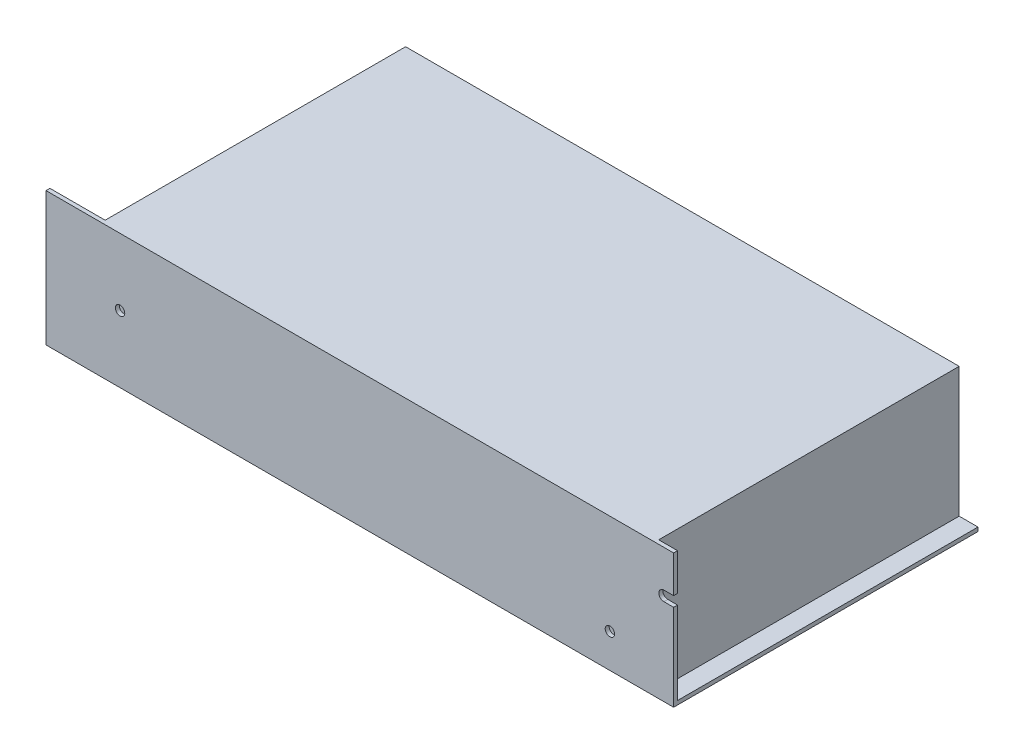
SolidWorks part; units mm, degrees
material "Stal węglowa"
ref_plane "Front" through (0, 0, 0) normal (0, 0, 1) x (1, 0, 0)
ref_plane "Top" through (0, 0, 0) normal (0, 1, 0) x (1, 0, 0)
ref_plane "Right" through (0, 0, 0) normal (1, 0, 0) x (0, 0, -1)
sketch "Szkic1" plane through (0, 0, 0) normal (0, 1, 0) x (1, 0, 0)
  line L1 (-60.5469, 54.8828) -> (139.4531, 54.8828)
  line L2 (-60.5469, 54.8828) -> (-60.5469, -42.1172)
  line L3 (-60.5469, -42.1172) -> (139.4531, -42.1172)
  line L4 (139.4531, 54.8828) -> (139.4531, -42.1172)
  dimension "D1" = 200
  dimension "D2" = 97
extrude "Dodanie-wyciągnięcie1" add sketch "Szkic1" along normal blind 1.25
sketch "Szkic2" plane through (0, 0, 0) normal (0, -1, 0) x (1, 0, 0)
  line L0 (-60.5469, 42.1172) -> (139.4531, 42.1172) construction
  line L1 (-60.5469, 42.1172) -> (139.4531, 42.1172)
  line L2 (-60.5469, 42.1172) -> (-60.5469, 40.8672)
  line L3 (-60.5469, 40.8672) -> (139.4531, 40.8672)
  line L4 (139.4531, 42.1172) -> (139.4531, 40.8672)
  line L5 (-60.5469, -54.8828) -> (-60.5469, 42.1172) construction
  line L6 (139.4531, 42.1172) -> (139.4531, -54.8828) construction
  dimension "D1" = 1.25
extrude "Dodanie-wyciągnięcie2" add sketch "Szkic2" against normal blind 42.6
sketch "Szkic3" plane through (0, 0, 42.1172) normal (0, 0, 1) x (1, 0, 0)
  line L0 (148.6314, 30.8) -> (134.7531, 30.8) construction
  line L1 (139.4531, 42.6) -> (-60.5469, 42.6) construction
  line L2 (151.1568, 27.6) -> (134.7531, 27.6) construction
  line L3 (134.7531, 30.8) -> (134.7531, 27.6) construction
  line L4 (139.4531, 42.6) -> (139.4531, 0) construction
  line L5 (134.7531, 29.2) -> (145.9475, 29.2) construction
  line L6 (136.3531, 26.4846) -> (136.3531, 33.5389) construction
  line L7 (136.3531, 30.8) -> (139.4531, 30.8)
  line L8 (139.4531, 30.8) -> (139.4531, 27.6)
  line L9 (139.4531, 27.6) -> (136.3531, 27.6)
  line L10 (120.6531, 73.2747) -> (120.6531, -18.7111) construction
  line L11 (63.995, 12.3) -> (238.0814, 12.3) construction
  line L12 (97.5718, 9.3) -> (153.7311, 9.3) construction
  line L13 (117.6531, 52.937) -> (117.6531, -10.3506) construction
  line L14 (120.6531, 9.3) -> (117.6531, 12.3) construction
  line L16 (-60.5469, 42.6) -> (-60.5469, 0) construction
  line L17 (-38.4469, 58.4899) -> (-38.4469, -5.7299) construction
  line L18 (-35.4469, 60.1177) -> (-35.4469, -5.7299) construction
  line L19 (-35.4469, 21.3) -> (-38.4469, 21.3) construction
  arc A2 (136.3531, 30.8) -> (136.3531, 27.6) centre (136.3531, 29.2) ccw
  circle A3 centre (119.1531, 10.8) radius 1.5
  circle A4 centre (-36.9469, 21.3) radius 1.5
  dimension "D1" = 11.8
  dimension "D2" = 3.2
  dimension "D3" = 4.7
  dimension "D4" = 1.6
  dimension "D5" = 18.8
  dimension "D6" = 30.3
  dimension "D7" = 3
  dimension "D8" = 3
  dimension "D9" = 22.1
  dimension "D10" = 3
sketch "Szkic4" plane through (0, 0, 0) normal (0, -1, 0) x (1, 0, 0)
  line L0 (123.1531, -54.8828) -> (123.1531, 47.2519) construction
  line L1 (139.4531, -54.8828) -> (-60.5469, -54.8828) construction
  line L2 (139.4531, 42.1172) -> (139.4531, -54.8828) construction
  line L3 (120.1531, 42.1172) -> (120.1531, -54.8828) construction
  line L4 (-60.5469, 42.1172) -> (139.4531, 42.1172) construction
  line L5 (139.4531, -6.3828) -> (-60.5469, -6.3828) construction
  line L6 (-60.5469, -54.8828) -> (-60.5469, 42.1172) construction
  line L7 (123.1531, -37.1328) -> (120.1531, -37.1328) construction
  line L8 (120.1531, -40.1328) -> (123.1531, -40.1328) construction
  line L9 (123.1531, 24.3672) -> (120.1531, 24.3672) construction
  line L10 (123.1531, -37.1328) -> (120.1531, -40.1328) construction
  line L11 (120.1531, 27.3672) -> (123.1531, 27.3672) construction
  line L12 (123.1531, 27.3672) -> (120.1531, 24.3672) construction
  line L13 (121.6531, -38.6328) -> (-104.4577, -38.6328) construction
  line L14 (121.6531, 25.8672) -> (-154.3123, 25.8672) construction
  line L15 (18.8531, -71.8578) -> (18.8531, 79.856) construction
  line L16 (120.1531, -40.379) -> (10.8847, -40.379) construction
  line L17 (120.1531, 24.3672) -> (10.8847, 24.3672) construction
  circle A1 centre (121.6531, -38.6328) radius 1.5
  circle A3 centre (121.6531, 25.8672) radius 1.5
  circle A5 centre (17.1069, -38.6328) radius 1.7462
  circle A7 centre (17.3531, 25.8672) radius 1.5
  dimension "D3" = 61.5
  dimension "D1" = 16.3
  dimension "D2" = 3
  dimension "D4" = 90
  dimension "D5" = 101.3
extrude "Wytnij-wyciągnięcie1" cut sketch "Szkic4" against normal up to surface (1.25 mm away) up to face at (39.4531, 1.25, -7.0078)
sketch "Szkic5" plane through (0, 1.25, 0) normal (0, 1, 0) x (1, 0, 0)
  line L0 (-42.9514, 54.8828) -> (-42.9514, -61.7896) construction
  line L1 (139.4531, 54.8828) -> (-60.5469, 54.8828) construction
  line L2 (-60.5469, 54.8828) -> (-60.5469, -40.8672) construction
  line L4 (-42.9514, 54.8828) -> (139.4531, 54.8828)
  line L5 (-42.9514, 54.8828) -> (-42.9514, -40.8672)
  line L6 (-42.9514, -40.8672) -> (139.4531, -40.8672)
  line L7 (139.4531, 54.8828) -> (139.4531, -40.8672)
  dimension "D1" = 17.5954
extrude "Dodanie-wyciągnięcie3" add sketch "Szkic5" along normal up to surface (41.35 mm away) up to face at (39.4531, 42.6, 41.4922)
sketch "Szkic6" plane through (0, 1.25, 0) normal (0, 1, 0) x (1, 0, 0)
  line L0 (-42.9514, 54.8828) -> (-42.9514, -40.8672) construction
  line L1 (-60.5469, 54.8828) -> (-42.9514, 54.8828)
  line L2 (-60.5469, 54.8828) -> (-60.5469, -34.0156)
  line L3 (-60.5469, -34.0156) -> (-42.9514, -34.0156)
  line L4 (-42.9514, 54.8828) -> (-42.9514, -34.0156)
extrude "Dodanie-wyciągnięcie4" add sketch "Szkic6" along normal blind 22
extrude "Wytnij-wyciągnięcie2" cut sketch "Szkic3" against normal up to surface (1.25 mm away) up to face at (-51.7492, 21.925, 40.8672)
sketch "Szkic7" plane through (139.4531, 0, 0) normal (1, 0, 0) x (0, 0, -1)
  line L0 (-42.1172, 1.25) -> (67.6419, 1.25) construction
  line L1 (-42.1172, 27.6) -> (-42.1172, 0) construction
  line L2 (-42.1172, 0) -> (54.8828, 0) construction
  line L3 (-40.8672, 42.6) -> (-40.8672, -6.4098) construction
  line L4 (54.8828, 42.6) -> (-42.1172, 42.6) construction
  line L6 (-40.8672, 1.25) -> (54.8828, 1.25)
  line L7 (-40.8672, 1.25) -> (-40.8672, 42.6)
  line L8 (-40.8672, 42.6) -> (54.8828, 42.6)
  line L9 (54.8828, 1.25) -> (54.8828, 42.6)
  dimension "D1" = 1.25
  dimension "D2" = 1.25
extrude "Wytnij-wyciągnięcie3" cut sketch "Szkic7" against normal blind 6
sketch "Szkic8" plane through (0, 0, 0) normal (0, -1, 0) x (1, 0, 0)
  line L0 (17.1069, -38.6328) -> (17.3531, 25.8672) construction
  line L1 (121.6531, -38.6328) -> (121.6531, 25.8672) construction
ref_plane "Płaszczyzna1" through (17.2541, 0, -0.0659) normal (-1, 0, 0.0038) x (0.0038, 0, 1)
ref_plane "Płaszczyzna2" through (121.6531, 0, 0) normal (-1, 0, 0) x (0, 0, 1)
